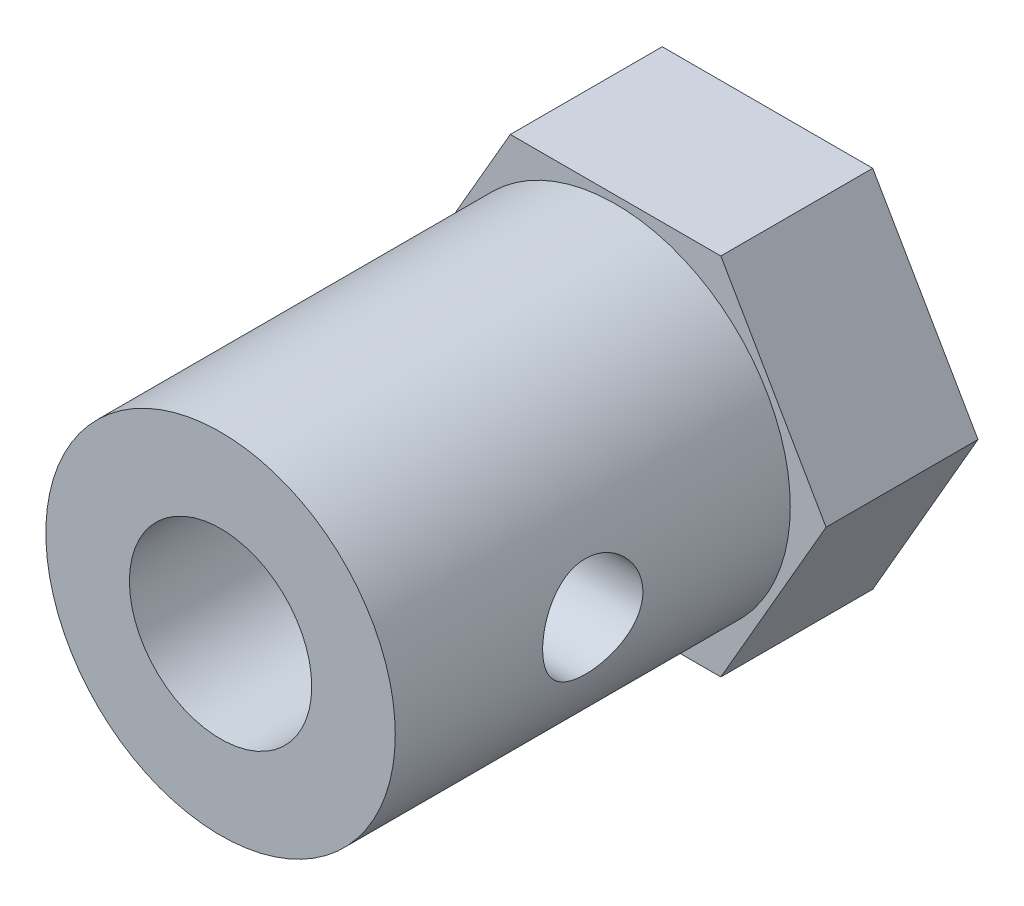
SolidWorks part; units mm, degrees
material "黄铜"
ref_plane "前视基准面" through (0, 0, 0) normal (0, 0, 1) x (1, 0, 0)
ref_plane "上视基准面" through (0, 0, 0) normal (0, 1, 0) x (1, 0, 0)
ref_plane "右视基准面" through (0, 0, 0) normal (1, 0, 0) x (0, 0, -1)
sketch "草图1" plane through (0, 0, 0) normal (0, 0, 1) x (1, 0, 0)
  line L1 (6.9282, 0) -> (3.4641, 6)
  line L2 (3.4641, 6) -> (-3.4641, 6)
  line L3 (-3.4641, 6) -> (-6.9282, 0)
  line L4 (-6.9282, 0) -> (-3.4641, -6)
  line L5 (-3.4641, -6) -> (3.4641, -6)
  line L6 (3.4641, -6) -> (6.9282, 0)
  circle A0 centre (0, 0) radius 6 construction
  circle A1 centre (0, 0) radius 2
  dimension "D1" = 4
  dimension "D2" = 12
extrude "轮毂端六角12mm_厚5_中心M4孔简化" add sketch "草图1" along normal blind 5
sketch "草图2" plane through (0, 0, 0) normal (0, 0, 1) x (1, 0, 0)
  circle A0 centre (0, 0) radius 5.75
  circle A1 centre (0, 0) radius 3
  dimension "D1" = 6
  dimension "D2" = 11.5
extrude "电机端_外径11.5_孔径6_长13" add sketch "草图2" along normal blind 13 from offset 5
sketch "草图3" plane through (0, 0, 0) normal (1, 0, 0) x (0, 0, -1)
  circle A0 centre (-11.5, 0) radius 1.65
extrude "M4紧定螺钉底孔_牙型简化" cut sketch "草图3" along normal through all and the other way through all
